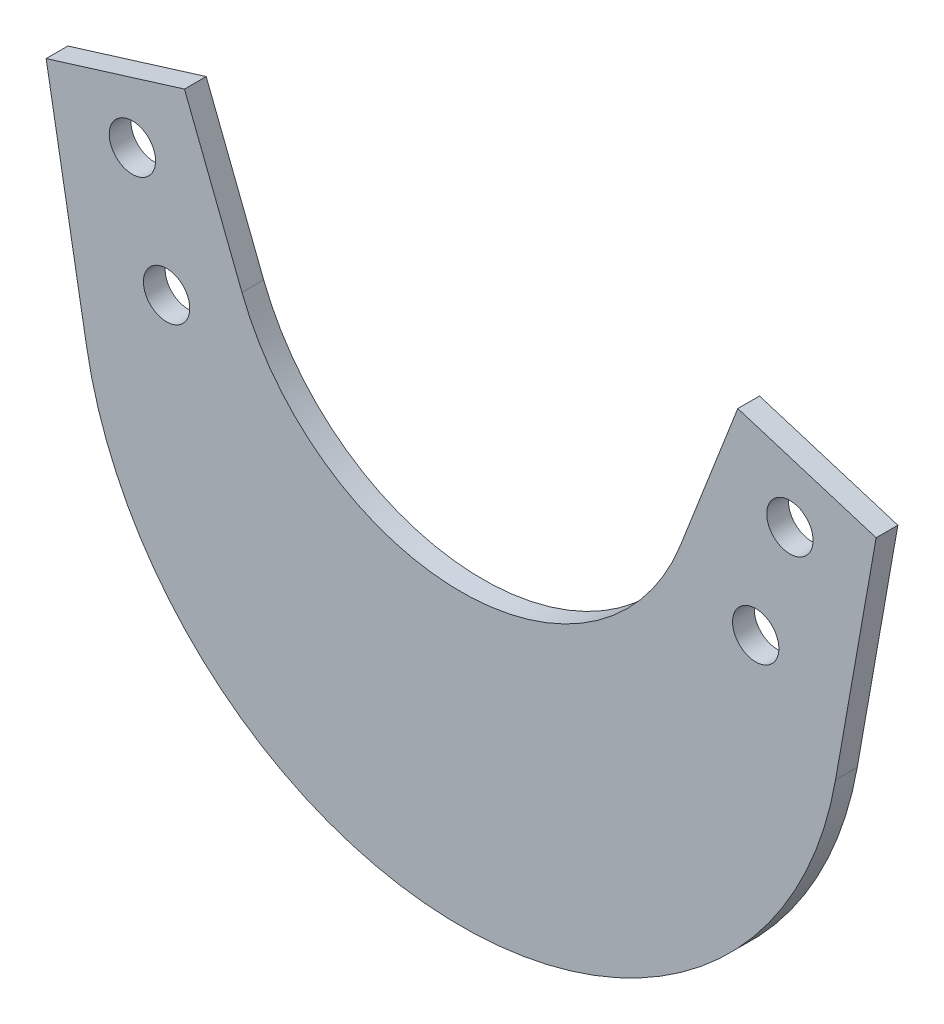
SolidWorks part; units mm, degrees
ref_plane "Front Plane" through (0, 0, 0) normal (0, 0, 1) x (1, 0, 0)
ref_plane "Top Plane" through (0, 0, 0) normal (0, 1, 0) x (1, 0, 0)
ref_plane "Right Plane" through (0, 0, 0) normal (1, 0, 0) x (0, 0, -1)
sketch "Sketch1" plane through (0, 0, 0) normal (0, 0, 1) x (1, 0, 0)
  line L0 (0, 0) -> (0, -36.249) construction
  line L1 (25.8597, -14.555) -> (28.6634, 1.3249) construction
  line L2 (22, 11.6893) -> (15.1385, -5.9041) construction
  line L3 (19.1087, 4.2759) -> (28.6634, 1.3249) construction
  line L4 (25.8597, -14.555) -> (28.6634, 1.3249)
  line L5 (19.1087, 4.2759) -> (15.1385, -5.9041)
  line L6 (19.1087, 4.2759) -> (28.6634, 1.3249)
  line L7 (19.8392, -0.1361) -> (17.4784, -7.7798) construction
  line L8 (23.2112, -9.5505) -> (25.572, -1.9068) construction
  line L9 (19.8392, -0.1361) -> (17.4784, -7.7798) construction
  line L10 (23.2112, -9.5505) -> (25.572, -1.9068) construction
  line L11 (-25.8597, -14.555) -> (-28.6634, 1.3249)
  line L12 (-19.1087, 4.2759) -> (-28.6634, 1.3249)
  line L13 (-19.1087, 4.2759) -> (-15.1385, -5.9041)
  line L14 (-23.2112, -9.5505) -> (-25.572, -1.9068) construction
  line L15 (-19.8392, -0.1361) -> (-17.4784, -7.7798) construction
  line L38 (0, 0) -> (16.249, 0) construction
  circle A0 centre (0, 0) radius 16.249 construction
  circle A1 centre (0, 0) radius 16.249 construction
  circle A2 centre (0, -9.9893) radius 26.2597 construction
  circle A3 centre (0, -9.9893) radius 26.2597 construction
  arc A4 (15.1385, -5.9041) -> (-15.1385, -5.9041) centre (0, 0) cw
  arc A5 (25.8597, -14.555) -> (-25.8597, -14.555) centre (0, -9.9893) cw
  arc A6 (25.572, -1.9068) -> (19.8392, -0.1361) centre (22.7056, -1.0214) ccw construction
  circle A7 centre (22.7056, -1.0214) radius 1.6 construction
  circle A8 centre (20.3448, -8.6652) radius 1.6 construction
  arc A9 (17.4784, -7.7798) -> (23.2112, -9.5505) centre (20.3448, -8.6652) ccw construction
  arc A10 (25.572, -1.9068) -> (19.8392, -0.1361) centre (22.7056, -1.0214) ccw construction
  circle A11 centre (-20.3448, -8.6652) radius 1.6
  circle A12 centre (-22.7056, -1.0214) radius 1.6
  arc A13 (-25.572, -1.9068) -> (-19.8392, -0.1361) centre (-22.7056, -1.0214) cw construction
  arc A14 (-17.4784, -7.7798) -> (-23.2112, -9.5505) centre (-20.3448, -8.6652) cw construction
  circle A16 centre (22.7056, -1.0214) radius 1.6
  circle A17 centre (20.3448, -8.6652) radius 1.6
  arc A18 (17.4784, -7.7798) -> (23.2112, -9.5505) centre (20.3448, -8.6652) ccw construction
extrude "Boss-Extrude1" add sketch "Sketch1" along normal blind 1.5
